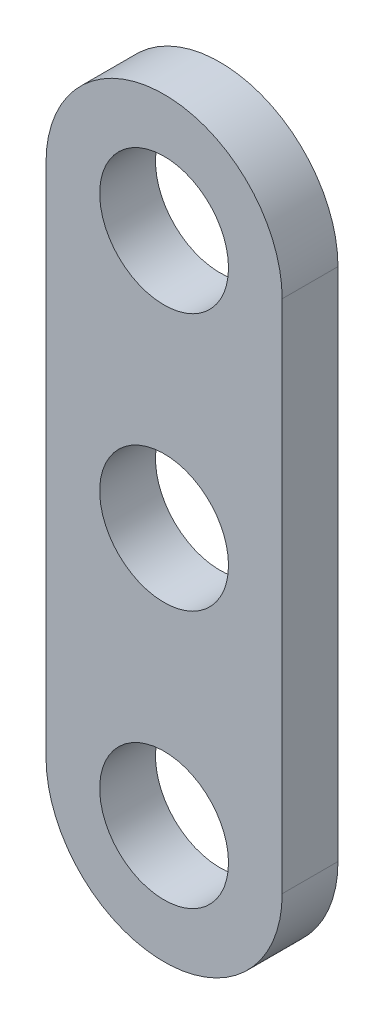
SolidWorks part; units mm, degrees
ref_plane "前视基准面" through (0, 0, 0) normal (0, 0, 1) x (1, 0, 0)
ref_plane "上视基准面" through (0, 0, 0) normal (0, 1, 0) x (1, 0, 0)
ref_plane "右视基准面" through (0, 0, 0) normal (1, 0, 0) x (0, 0, -1)
sketch "草图1" plane through (0, 0, 0) normal (0, 0, 1) x (1, 0, 0)
  line L0 (0, 12) -> (0, -12) construction
  line L1 (5.5, 12) -> (5.5, -12)
  line L2 (-5.5, 12) -> (-5.5, -12)
  arc A0 (5.5, 12) -> (-5.5, 12) centre (0, 12) ccw
  arc A1 (-5.5, -12) -> (5.5, -12) centre (0, -12) ccw
  circle A2 centre (0, -12) radius 3
  circle A3 centre (0, 0) radius 3
  circle A4 centre (0, 12) radius 3
  point P2 (0, 0)
  dimension "D2" = 5.5
  dimension "D3" = 6
  dimension "D1" = 24
extrude "凸台-拉伸1" add sketch "草图1" along normal blind 2.6
